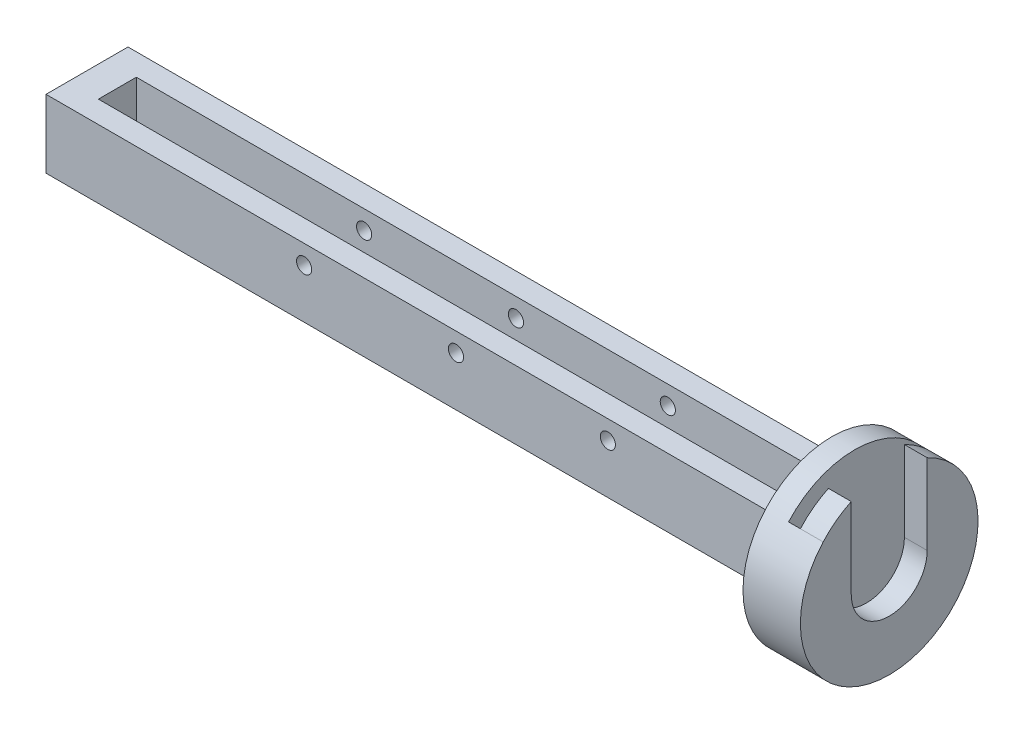
SolidWorks part; units mm, degrees
ref_plane "Front Plane" through (0, 0, 0) normal (0, 0, 1) x (1, 0, 0)
ref_plane "Top Plane" through (0, 0, 0) normal (0, 1, 0) x (1, 0, 0)
ref_plane "Right Plane" through (0, 0, 0) normal (1, 0, 0) x (0, 0, -1)
sketch "Sketch1" plane through (0, 0, 0) normal (1, 0, 0) x (0, 0, -1)
  line L1 (0, 0) -> (10.8, 0)
  line L2 (0, 0) -> (0, 9)
  line L3 (0, 9) -> (10.8, 9)
  line L4 (10.8, 0) -> (10.8, 9)
extrude "Boss-Extrude1" add sketch "Sketch1" along normal blind 4
sketch "Sketch2" plane through (4, 0, 0) normal (1, 0, 0) x (0, 0, -1)
  line L0 (0, 9) -> (0, 0)
  line L1 (0, 0) -> (10.8, 0)
  line L2 (10.8, 0) -> (10.8, 9)
  line L3 (10.8, 9) -> (7.9, 9)
  line L4 (10.8, 9) -> (0, 9) construction
  line L5 (7.9, 9) -> (7.9, 3)
  line L6 (7.9, 3) -> (2.9, 3)
  line L7 (2.9, 3) -> (2.9, 9)
  line L8 (2.9, 9) -> (0, 9)
extrude "Boss-Extrude2" add sketch "Sketch2" along normal blind 90
sketch "Sketch3" plane through (94, 0, 0) normal (1, 0, 0) x (0, 0, -1)
  line L1 (0, 9) -> (10.8, 9)
  line L2 (0, 9) -> (0, 0)
  line L3 (0, 0) -> (10.8, 0)
  line L4 (10.8, 9) -> (10.8, 0)
extrude "Boss-Extrude3" add sketch "Sketch3" along normal blind 4
sketch "Sketch4" plane through (98, 0, 0) normal (1, 0, 0) x (0, 0, -1)
  circle A0 centre (5.5, 4.5) radius 11.7
extrude "Boss-Extrude4" add sketch "Sketch4" along normal blind 3
sketch "Sketch5" plane through (101, 0, 0) normal (1, 0, 0) x (0, 0, -1)
  line L1 (-3.2, 4.5) -> (-3.2, 12.323)
  line L3 (14.2, 4.5) -> (14.2, 12.323)
  circle A1 centre (5.5, 4.5) radius 11.7 construction
  arc A2 (-3.2, 4.5) -> (14.2, 4.5) centre (5.5, 4.5) ccw
  arc A3 (-3.2, 12.323) -> (14.2, 12.323) centre (5.5, 4.5) ccw
extrude "Boss-Extrude5" add sketch "Sketch5" along normal blind 1.56
sketch "Sketch6" plane through (102.56, 0, 0) normal (1, 0, 0) x (0, 0, -1)
  line L0 (0.5, 4.5) -> (0.5, 15.0778)
  line L1 (10.5, 4.5) -> (10.5, 15.0778)
  arc A1 (14.2, 12.323) -> (-3.2, 12.323) centre (5.5, 4.5) ccw construction
  arc A2 (0.5, 15.0778) -> (10.5, 15.0778) centre (5.5, 4.5) ccw
  arc A3 (0.5, 4.5) -> (10.5, 4.5) centre (5.5, 4.5) ccw
extrude "Boss-Extrude6" add sketch "Sketch6" along normal blind 3
sketch "Sketch7" plane through (0, 0, 0) normal (0, 0, 1) x (1, 0, 0)
  circle A0 centre (34, 6.5) radius 1
  circle A1 centre (54, 6.5) radius 1
  circle A2 centre (74, 6.5) radius 1
  point P0 (0, 0)
extrude "Cut-Extrude2" cut sketch "Sketch7" against normal blind 11
